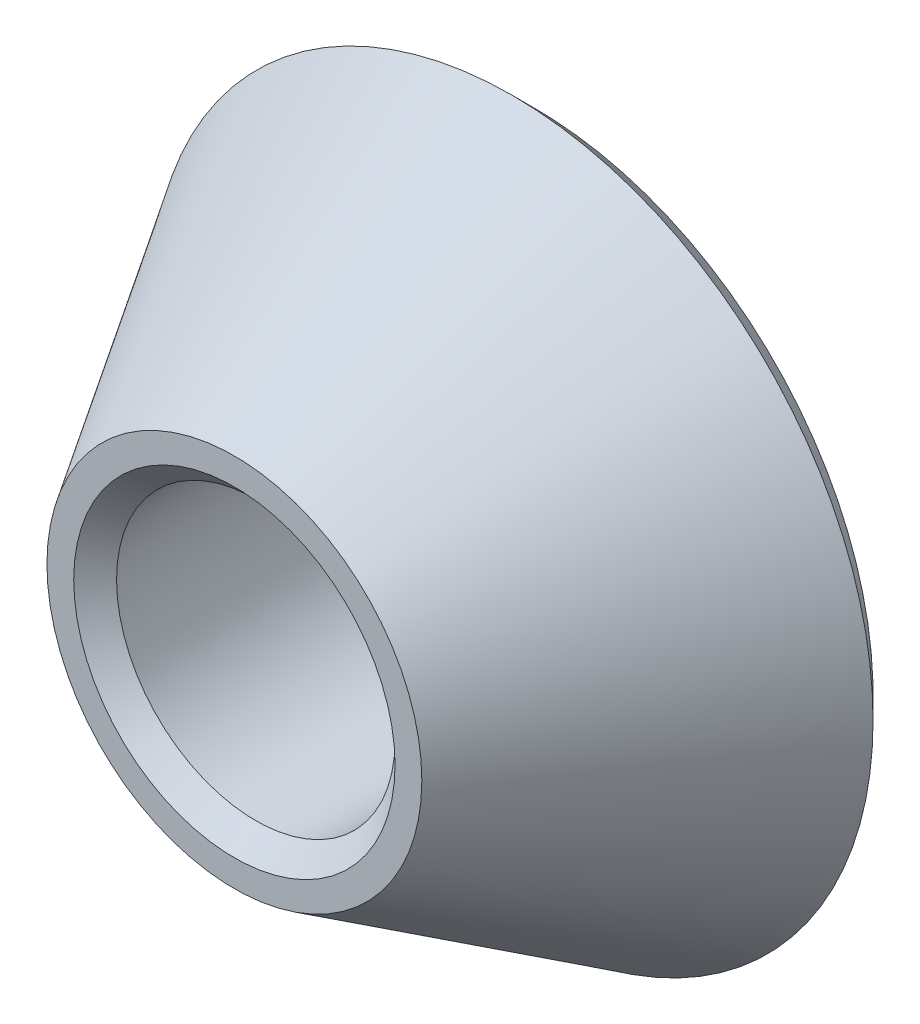
SolidWorks part; units mm, degrees
ref_plane "Front" through (0, 0, 0) normal (0, 0, 1) x (1, 0, 0)
ref_plane "Top" through (0, 0, 0) normal (0, 1, 0) x (1, 0, 0)
ref_plane "Right" through (0, 0, 0) normal (1, 0, 0) x (0, 0, -1)
sketch "Skizze5" plane through (0, 0, 0) normal (1, 0, 0) x (0, 0, -1)
  line L0 (0, 2.6) -> (-5.6, 2.6)
  line L1 (-5.6, 2.6) -> (-5.6, 3.5)
  line L2 (-5.6, 3.5) -> (-0.4151, 6.7406)
  line L3 (0, 6.3255) -> (0, 2.6)
  line L4 (0, 0) -> (-6.7737, 0) construction
  line L5 (0, 6.3255) -> (-0.4151, 6.7406)
  line L6 (0, 7) -> (0, 6.3255) construction
  line L7 (-0.4151, 6.7406) -> (0, 7) construction
  dimension "D1" = 5.6
  dimension "D2" = 5.2
  dimension "D3" = 7
  dimension "D4" = 14
  dimension "D5" = 45
revolve "Rotation1" add sketch "Skizze5" angle 360 about L4
chamfer "Fase1" distance 0.4 angle 45 2 edges at (-2.6, 0, 5.6) (-2.6, 0, 0)
